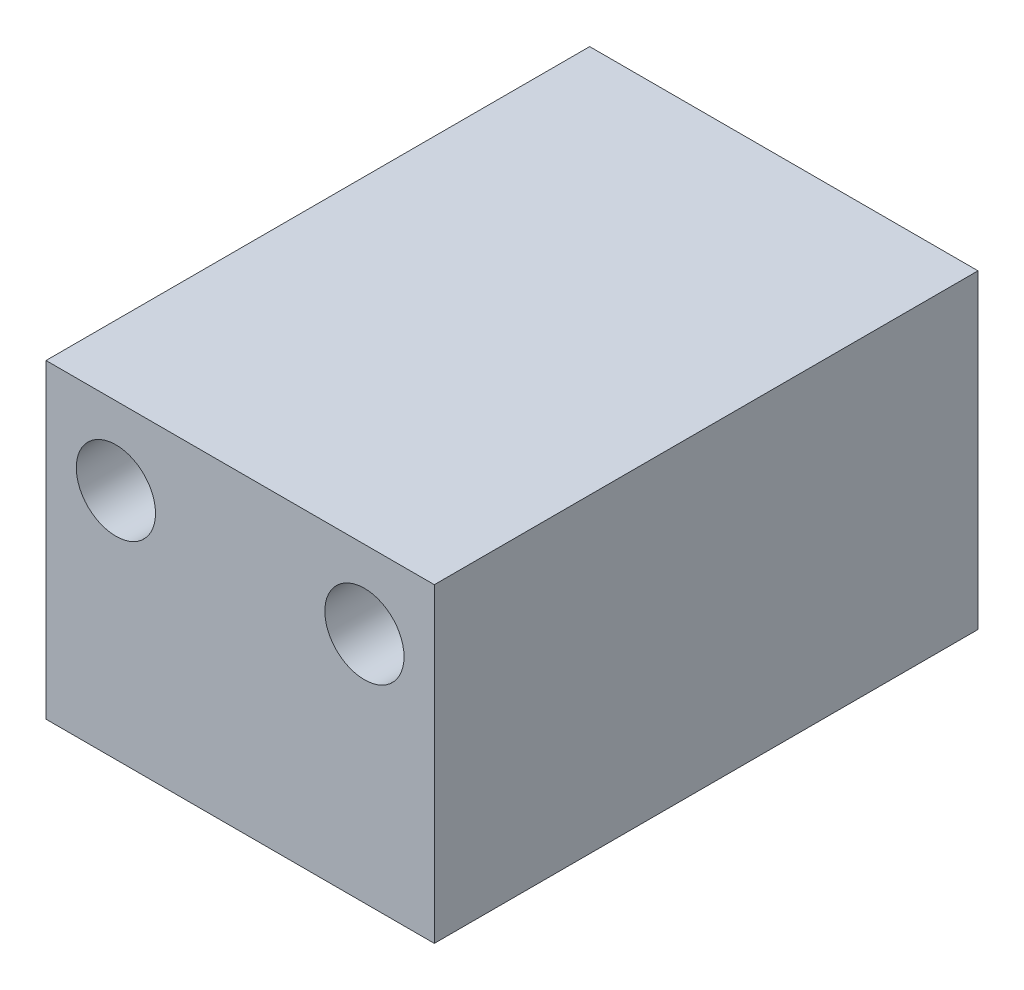
SolidWorks part; units mm, degrees
material "Brass"
ref_plane "Front" through (0, 0, 0) normal (0, 0, 1) x (1, 0, 0)
ref_plane "Top" through (0, 0, 0) normal (0, 1, 0) x (1, 0, 0)
ref_plane "Right" through (0, 0, 0) normal (1, 0, 0) x (0, 0, -1)
sketch "Sketch1" plane through (0, 0, 0) normal (0, 1, 0) x (1, 0, 0)
  line L1 (0, 0) -> (25, 0)
  line L2 (0, 0) -> (0, 35)
  line L3 (0, 35) -> (25, 35)
  line L4 (25, 0) -> (25, 35)
  dimension "D1" = 25
  dimension "D2" = 35
extrude "Boss-Extrude1" add sketch "Sketch1" along normal blind 20
sketch "Sketch3" plane through (0, 0, 0) normal (0, 0, 1) x (1, 0, 0)
  line L0 (4.5, 15) -> (20.5, 15) construction
  line L1 (0, 0) -> (25, 0) construction
  line L2 (12.5, 20) -> (12.5, 15) construction
  line L3 (0, 20) -> (25, 20) construction
  circle A0 centre (4.5, 15) radius 2.55
  circle A1 centre (20.5, 15) radius 2.55
  dimension "D1" = 5.1
  dimension "D3" = 16
  dimension "D2" = 15
extrude "Cut-Extrude2" cut sketch "Sketch3" against normal through all
sketch "Sketch4" plane through (0, 0, 0) normal (0, -1, 0) x (1, 0, 0)
  line L0 (12.5, -5) -> (12.5, -35) construction
  line L1 (25, -35) -> (0, -35) construction
  circle A0 centre (12.5, -5) radius 2.25
  circle A1 centre (12.5, -30) radius 2.25
  dimension "D1" = 4.5
  dimension "D2" = 25
  dimension "D3" = 5
extrude "Cut-Extrude3" cut sketch "Sketch4" against normal blind 10
cosmetic thread "Cosmetic Thread1" parameters "D2"=6
cosmetic thread "Cosmetic Thread2" parameters "D2"=6
